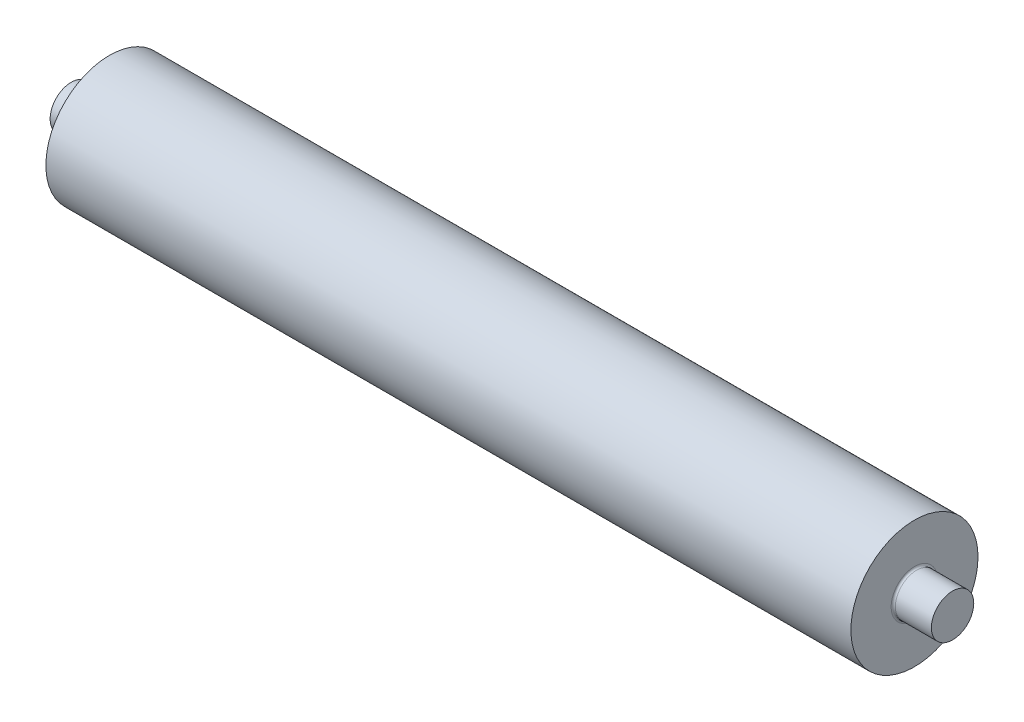
SolidWorks part; units mm, degrees
ref_plane "Front Plane" through (0, 0, 0) normal (0, 0, 1) x (1, 0, 0)
ref_plane "Top Plane" through (0, 0, 0) normal (0, 1, 0) x (1, 0, 0)
ref_plane "Right Plane" through (0, 0, 0) normal (1, 0, 0) x (0, 0, -1)
sketch "Sketch1" plane through (0, 0, 0) normal (0, 1, 0) x (1, 0, 0)
  line L0 (0, 0) -> (0, 406.6158) construction
  line L1 (1040, 0) -> (-1040, 0)
  line L2 (-1040, 0) -> (-1040, 50)
  line L3 (-1040, 50) -> (-950, 50)
  line L4 (-950, 50) -> (-950, 150)
  line L5 (-950, 150) -> (950, 150)
  line L6 (1040, 0) -> (1040, 50)
  line L7 (1040, 50) -> (950, 50)
  line L8 (950, 50) -> (950, 150)
  point P12 (0, 150)
  dimension "D1" = 2080
  dimension "D2" = 50
  dimension "D3" = 150
  dimension "D4" = 950
revolve "Revolve1" add sketch "Sketch1" angle 360 about L1
fillet "Fillet1" radius 5 2 edges at (950, 0, -50) (-950, 0, -50)
